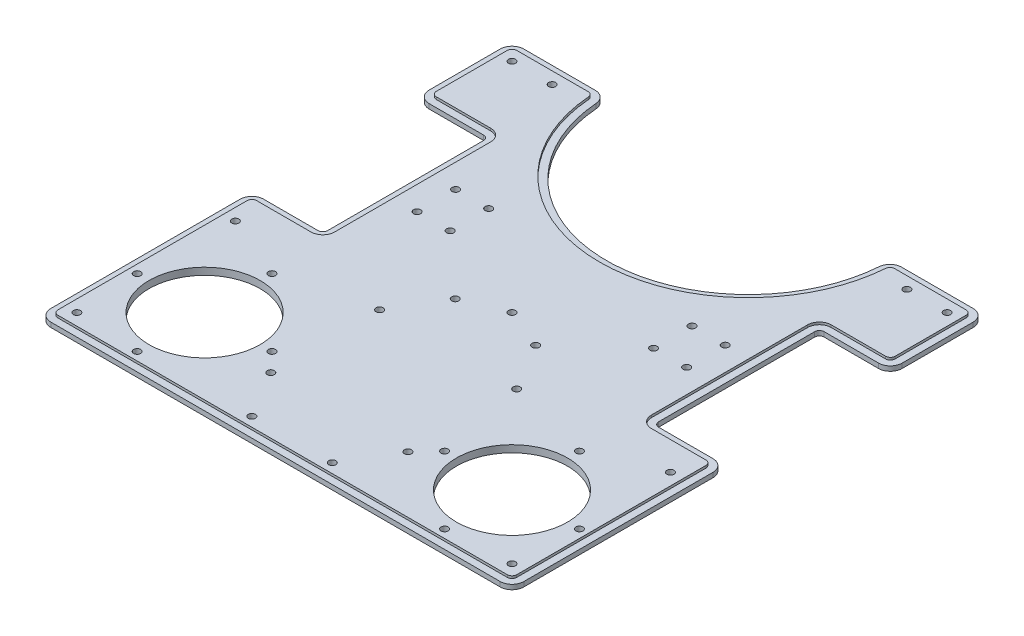
SolidWorks part; units mm, degrees
ref_plane "Front Plane" through (0, 0, 0) normal (0, 0, 1) x (1, 0, 0)
ref_plane "Top Plane" through (0, 0, 0) normal (0, 1, 0) x (1, 0, 0)
ref_plane "Right Plane" through (0, 0, 0) normal (1, 0, 0) x (0, 0, -1)
sketch "Sketch1" plane through (0, 0, 0) normal (0, 1, 0) x (1, 0, 0)
  line L0 (0, 100) -> (0, -100)
  line L1 (-100, -100) -> (100, -100)
  line L2 (-100, -100) -> (-100, 100)
  line L3 (-100, 100) -> (100, 100)
  line L4 (100, -100) -> (100, 100)
  line L5 (-100, -100) -> (100, 100) construction
  line L6 (-100, 100) -> (100, -100) construction
  line L7 (0, 0) -> (100, 0)
  line L8 (70, 25) -> (37.5, 25)
  line L9 (100, 60) -> (70, 60)
  line L10 (100, 60) -> (100, -10)
  line L11 (100, -10) -> (70, -10)
  line L12 (70, 60) -> (70, -10)
  line L13 (100, -65) -> (65, -65)
  line L14 (5, 11.85) -> (70, 11.85)
  line L15 (5, 11.85) -> (5, 38.15)
  line L16 (5, 38.15) -> (70, 38.15)
  line L17 (70, 11.85) -> (70, 38.15)
  line L18 (5, 11.85) -> (70, 38.15) construction
  line L19 (5, 38.15) -> (70, 11.85) construction
  line L20 (0, -50) -> (29, -50)
  line L21 (29, -93) -> (-29, -93)
  line L22 (29, -93) -> (29, -7)
  line L23 (29, -7) -> (-29, -7)
  line L24 (-29, -93) -> (-29, -7)
  line L25 (29, -93) -> (-29, -7) construction
  line L26 (29, -7) -> (-29, -93) construction
  line L27 (35, 38.15) -> (35, 11.85)
  line L28 (43, 38.15) -> (43, 11.85)
  line L29 (68, 11.85) -> (35, 11.85)
  line L30 (68, 11.85) -> (68, 38.15)
  line L31 (68, 38.15) -> (35, 38.15)
  line L32 (35, 11.85) -> (35, 38.15)
  line L33 (68, 11.85) -> (35, 38.15) construction
  line L34 (68, 38.15) -> (35, 11.85) construction
  line L35 (57, 38.15) -> (57, 11.85)
  line L36 (50, 38.15) -> (50, 11.85)
  line L37 (57, 38.15) -> (43, 38.15)
  line L38 (57, 38.15) -> (57, 11.85)
  line L39 (57, 11.85) -> (43, 11.85)
  line L40 (43, 38.15) -> (43, 11.85)
  circle A0 centre (0, 100) radius 60
  circle A1 centre (65, -65) radius 23.5
  circle A2 centre (65, -65) radius 28.5
  circle A3 centre (93.5, -65) radius 1.5
  circle A4 centre (17, -93) radius 1.5
  circle A5 centre (29, -73) radius 1.5
  circle A6 centre (57, 16.85) radius 1.5
  circle A7 centre (92, -92) radius 1.5
  circle A8 centre (92, -25) radius 1.5
  circle A9 centre (92, 92) radius 1.5
  circle A10 centre (75, 92) radius 1.5
  circle A11 centre (0, 0) radius 1.5
  point P0 (0, 0)
  point P27 (0, -50)
  point P40 (51.5, 25)
  dimension "D3" = 120
  dimension "D9" = 47
  dimension "D10" = 57
  dimension "D11" = 3
  dimension "D17" = 3
  dimension "D18" = 3
  dimension "D25" = 3
  dimension "D27" = 3
  dimension "D29" = 3
  dimension "D32" = 3
  dimension "D33" = 3
  dimension "D37" = 3
  dimension "D1" = 200
  dimension "D2" = 200
  dimension "D4" = 70
  dimension "D5" = 30
  dimension "D6" = 95
  dimension "D7" = 26.3
  dimension "D8" = 10
  dimension "D12" = 35
  dimension "D13" = 35
  dimension "D14" = 86
  dimension "D15" = 58
  dimension "D16" = 50
  dimension "D19" = 20
  dimension "D20" = 12
  dimension "D21" = 65
  dimension "D22" = 33
  dimension "D23" = 8
  dimension "D24" = 22
  dimension "D26" = 5
  dimension "D28" = 8
  dimension "D30" = 8
  dimension "D31" = 25
  dimension "D34" = 8
  dimension "D35" = 8
  dimension "D36" = 25
sketch "Sketch2" plane through (0, 0, 0) normal (0, 1, 0) x (1, 0, 0)
  line L0 (70, 25) -> (37.5, 25) construction
  line L1 (0, 0) -> (100, 0) construction
  line L2 (0, 100) -> (0, -100) construction
  line L3 (100, -65) -> (65, -65) construction
  line L4 (100, 60) -> (70, 60)
  line L5 (70, 60) -> (70, -10)
  line L6 (70, -10) -> (100, -10)
  line L7 (100, -10) -> (100, 60)
  line L8 (100, 60) -> (70, 60)
  line L9 (70, 60) -> (70, -10)
  line L10 (70, -10) -> (100, -10)
  line L11 (100, -10) -> (100, 60)
  line L12 (-100, -100) -> (100, -100)
  line L13 (100, -100) -> (100, 100)
  line L14 (100, 100) -> (-100, 100)
  line L15 (-100, 100) -> (-100, -100)
  line L16 (-100, -100) -> (100, -100)
  line L17 (100, -100) -> (100, 100)
  line L18 (100, 100) -> (60, 100)
  line L19 (-100, 100) -> (-100, -100)
  line L20 (-29, -93) -> (29, -93)
  line L21 (-29, -7) -> (-29, -93)
  line L22 (29, -7) -> (-29, -7)
  line L23 (29, -93) -> (29, -7)
  line L24 (-29, -93) -> (29, -93)
  line L25 (-29, -7) -> (-29, -93)
  line L26 (29, -7) -> (-29, -7)
  line L27 (29, -93) -> (29, -7)
  line L28 (5, 11.85) -> (70, 11.85)
  line L29 (70, 11.85) -> (70, 38.15)
  line L30 (70, 38.15) -> (5, 38.15)
  line L31 (5, 38.15) -> (5, 11.85)
  line L32 (5, 11.85) -> (70, 11.85)
  line L33 (70, 11.85) -> (70, 38.15)
  line L34 (70, 38.15) -> (5, 38.15)
  line L35 (5, 38.15) -> (5, 11.85)
  line L36 (57, 38.15) -> (57, 11.85) construction
  line L37 (57, 38.15) -> (57, 11.85) construction
  line L38 (57, 11.85) -> (43, 11.85) construction
  line L39 (57, 38.15) -> (43, 38.15) construction
  line L40 (43, 38.15) -> (43, 11.85) construction
  line L41 (43, 38.15) -> (43, 11.85) construction
  line L42 (35, 38.15) -> (35, 11.85) construction
  line L43 (68, 11.85) -> (35, 11.85) construction
  line L44 (68, 11.85) -> (68, 38.15) construction
  line L45 (68, 38.15) -> (35, 38.15) construction
  line L46 (35, 11.85) -> (35, 38.15) construction
  line L47 (0, -50) -> (29, -50) construction
  line L48 (50, 38.15) -> (50, 11.85) construction
  line L49 (70, 25) -> (37.5, 25)
  line L50 (0, 0) -> (100, 0)
  line L51 (0, 40) -> (0, -100)
  line L52 (100, -65) -> (65, -65)
  line L53 (57, 38.15) -> (57, 11.85)
  line L54 (57, 38.15) -> (57, 11.85)
  line L55 (57, 11.85) -> (43, 11.85)
  line L56 (57, 38.15) -> (43, 38.15)
  line L57 (43, 38.15) -> (43, 11.85)
  line L58 (43, 38.15) -> (43, 11.85)
  line L59 (35, 38.15) -> (35, 11.85)
  line L60 (68, 11.85) -> (35, 11.85)
  line L61 (68, 11.85) -> (68, 38.15)
  line L62 (68, 38.15) -> (35, 38.15)
  line L63 (35, 11.85) -> (35, 38.15)
  line L64 (0, -50) -> (29, -50)
  line L65 (50, 38.15) -> (50, 11.85)
  line L66 (-60, 100) -> (-100, 100)
  circle A1 centre (0, 100) radius 60
  arc A2 (-60, 100) -> (60, 100) centre (0, 100) ccw
  circle A3 centre (93.5, -65) radius 1.5
  circle A4 centre (93.5, -65) radius 1.5
  circle A5 centre (65, -65) radius 28.5
  circle A6 centre (65, -65) radius 28.5
  circle A7 centre (65, -65) radius 23.5
  circle A8 centre (65, -65) radius 23.5
  circle A9 centre (29, -73) radius 1.5
  circle A10 centre (29, -73) radius 1.5
  circle A11 centre (17, -93) radius 1.5
  circle A12 centre (17, -93) radius 1.5
  circle A13 centre (0, 0) radius 1.5
  circle A14 centre (0, 0) radius 1.5
  circle A15 centre (75, 92) radius 1.5
  circle A16 centre (75, 92) radius 1.5
  circle A17 centre (92, 92) radius 1.5
  circle A18 centre (92, 92) radius 1.5
  circle A19 centre (92, -25) radius 1.5
  circle A20 centre (92, -25) radius 1.5
  circle A21 centre (92, -92) radius 1.5
  circle A22 centre (92, -92) radius 1.5
  circle A23 centre (57, 16.85) radius 1.5
  circle A24 centre (57, 16.85) radius 1.5
  dimension "D1" = 0
  dimension "D2" = 0
  dimension "D3" = 0
  dimension "D4" = 0
  dimension "D5" = 0
  dimension "D6" = 0
  dimension "D7" = 0
  dimension "D8" = 0
  dimension "D9" = 0
  dimension "D10" = 0
  dimension "D11" = 0
  dimension "D12" = 0
  dimension "D13" = 0
  dimension "D14" = 0
  dimension "D15" = 0
  dimension "D16" = 0
sketch "Sketch3" plane through (0, 0, 0) normal (0, 1, 0) x (1, 0, 0)
  line L1 (-100, 100) -> (100, 100)
  line L2 (-100, 100) -> (-100, -100)
  line L3 (-100, -100) -> (100, -100)
  line L4 (100, 100) -> (100, -100)
extrude "Boss-Extrude1" add sketch "Sketch3" along normal blind 3
sketch "Sketch4" plane through (0, 3, 0) normal (0, 1, 0) x (1, 0, 0)
  line L0 (-100, -100) -> (100, 100) construction
  line L8 (-100, 100) -> (100, 100) construction
  line L9 (70, 60) -> (100, 60)
  line L10 (70, 60) -> (70, -10)
  line L11 (70, -10) -> (100, -10)
  line L12 (100, 60) -> (100, -10)
  circle A0 centre (92, 92) radius 1.5
  circle A1 centre (92, -92) radius 1.5
  circle A2 centre (-92, -92) radius 1.5
  circle A3 centre (-92, 92) radius 1.5
  circle A4 centre (92, -25) radius 1.5
  circle A5 centre (93.5, -65) radius 1.5
  circle A6 centre (17, -93) radius 1.5
  circle A7 centre (29, -73) radius 1.5
  circle A8 centre (75, 92) radius 1.5
  circle A9 centre (29, -27) radius 1.5
  circle A10 centre (17, -7) radius 1.5
  circle A11 centre (-92, -25) radius 1.5
  circle A12 centre (-17, -93) radius 1.5
  circle A13 centre (-29, -73) radius 1.5
  circle A14 centre (-29, -27) radius 1.5
  circle A15 centre (-17, -7) radius 1.5
  circle A16 centre (65, -65) radius 23.5
  circle A17 centre (65, -93.5) radius 1.5
  circle A18 centre (36.5, -65) radius 1.5
  circle A19 centre (65, -36.5) radius 1.5
  circle A20 centre (57, 16.85) radius 1.5
  circle A21 centre (57, 33.15) radius 1.5
  circle A22 centre (43, 16.85) radius 1.5
  circle A23 centre (43, 33.15) radius 1.5
  circle A24 centre (0, 100) radius 60
  circle A25 centre (-75, 92) radius 1.5
  circle A26 centre (0, 0) radius 1.5
  point P12 (0, 0)
  point P70 (65, -65)
  dimension "D1" = 4
  dimension "D2" = 4
extrude "Cut-Extrude1" cut sketch "Sketch4" against normal blind 5
ref_plane "Plane1" through (0, 0, 0) normal (-1, 0, 0) x (0, 0, 1)
mirror "Mirror1" about plane through (0, 0, 0) normal (-1, 0, 0) of "Cut-Extrude1"
fillet "Fillet1" radius 5 10 edges at (-100, 1.5, 100) (-100, 1.5, 10) (-100, 1.5, -60) (-100, 1.5, -100) (-60, 1.5, -100) (60, 1.5, -100) (100, 1.5, -60) (100, 1.5, -100) (100, 1.5, 100) (100, 1.5, 10)
fillet "Fillet2" radius 2 4 edges at (-70, 1.5, 10) (-70, 1.5, -60) (70, 1.5, -60) (70, 1.5, 10)
sketch "Sketch5" plane through (0, 3, 0) normal (0, 1, 0) x (1, 0, 0)
  line L0 (-97, 95) -> (-97, 65)
  line L1 (-95, 63) -> (-72, 63)
  line L2 (-67, 58) -> (-67, -8)
  line L3 (-72, -13) -> (-95, -13)
  line L4 (-97, -15) -> (-97, -95)
  line L5 (-95, -97) -> (95, -97)
  line L6 (97, -95) -> (97, -15)
  line L7 (95, -13) -> (72, -13)
  line L8 (67, -8) -> (67, 58)
  line L9 (72, 63) -> (95, 63)
  line L10 (97, 65) -> (97, 95)
  line L11 (95, 97) -> (64.8074, 97)
  line L12 (-64.8074, 97) -> (-95, 97)
  line L13 (-95, -100) -> (95, -100)
  line L14 (100, -95) -> (100, -15)
  line L15 (95, -10) -> (72, -10)
  line L16 (70, -8) -> (70, 58)
  line L17 (72, 60) -> (95, 60)
  line L18 (100, 65) -> (100, 95)
  line L19 (95, 100) -> (64.8074, 100)
  line L20 (-64.8074, 100) -> (-95, 100)
  line L21 (-100, 95) -> (-100, 65)
  line L22 (-95, 60) -> (-72, 60)
  line L23 (-70, 58) -> (-70, -8)
  line L24 (-72, -10) -> (-95, -10)
  line L25 (-100, -15) -> (-100, -95)
  line L26 (-95, -100) -> (95, -100)
  line L27 (100, -95) -> (100, -15)
  line L28 (95, -10) -> (72, -10)
  line L29 (70, -8) -> (70, 58)
  line L30 (72, 60) -> (95, 60)
  line L31 (100, 65) -> (100, 95)
  line L32 (95, 100) -> (64.8074, 100)
  line L33 (-64.8074, 100) -> (-95, 100)
  line L34 (-100, 95) -> (-100, 65)
  line L35 (-95, 60) -> (-72, 60)
  line L36 (-70, 58) -> (-70, -8)
  line L37 (-72, -10) -> (-95, -10)
  line L38 (-100, -15) -> (-100, -95)
  arc A0 (-97, 65) -> (-95, 63) centre (-95, 65) ccw
  arc A1 (-67, 58) -> (-72, 63) centre (-72, 58) ccw
  arc A2 (-72, -13) -> (-67, -8) centre (-72, -8) ccw
  arc A3 (-95, -13) -> (-97, -15) centre (-95, -15) ccw
  arc A4 (-97, -95) -> (-95, -97) centre (-95, -95) ccw
  arc A5 (95, -97) -> (97, -95) centre (95, -95) ccw
  arc A6 (97, -15) -> (95, -13) centre (95, -15) ccw
  arc A7 (67, -8) -> (72, -13) centre (72, -8) ccw
  arc A8 (72, 63) -> (67, 58) centre (72, 58) ccw
  arc A9 (95, 63) -> (97, 65) centre (95, 65) ccw
  arc A10 (97, 95) -> (95, 97) centre (95, 95) ccw
  arc A11 (64.8074, 97) -> (62.8133, 95.1538) centre (64.8074, 95) ccw
  arc A12 (-62.8133, 95.1538) -> (62.8133, 95.1538) centre (0, 100) ccw
  arc A13 (-62.8133, 95.1538) -> (-64.8074, 97) centre (-64.8074, 95) ccw
  arc A14 (-95, 97) -> (-97, 95) centre (-95, 95) ccw
  arc A15 (95, -100) -> (100, -95) centre (95, -95) ccw
  arc A16 (100, -15) -> (95, -10) centre (95, -15) ccw
  arc A17 (70, -8) -> (72, -10) centre (72, -8) ccw
  arc A18 (72, 60) -> (70, 58) centre (72, 58) ccw
  arc A19 (95, 60) -> (100, 65) centre (95, 65) ccw
  arc A20 (100, 95) -> (95, 100) centre (95, 95) ccw
  arc A21 (64.8074, 100) -> (59.8222, 95.3846) centre (64.8074, 95) ccw
  arc A22 (-59.8222, 95.3846) -> (59.8222, 95.3846) centre (0, 100) ccw
  arc A23 (-59.8222, 95.3846) -> (-64.8074, 100) centre (-64.8074, 95) ccw
  arc A24 (-95, 100) -> (-100, 95) centre (-95, 95) ccw
  arc A25 (-100, 65) -> (-95, 60) centre (-95, 65) ccw
  arc A26 (-70, 58) -> (-72, 60) centre (-72, 58) ccw
  arc A27 (-72, -10) -> (-70, -8) centre (-72, -8) ccw
  arc A28 (-95, -10) -> (-100, -15) centre (-95, -15) ccw
  arc A29 (-100, -95) -> (-95, -100) centre (-95, -95) ccw
  arc A30 (95, -100) -> (100, -95) centre (95, -95) ccw
  arc A31 (100, -15) -> (95, -10) centre (95, -15) ccw
  arc A32 (70, -8) -> (72, -10) centre (72, -8) ccw
  arc A33 (72, 60) -> (70, 58) centre (72, 58) ccw
  arc A34 (95, 60) -> (100, 65) centre (95, 65) ccw
  arc A35 (100, 95) -> (95, 100) centre (95, 95) ccw
  arc A36 (64.8074, 100) -> (59.8222, 95.3846) centre (64.8074, 95) ccw
  arc A37 (-59.8222, 95.3846) -> (59.8222, 95.3846) centre (0, 100) ccw
  arc A38 (-59.8222, 95.3846) -> (-64.8074, 100) centre (-64.8074, 95) ccw
  arc A39 (-95, 100) -> (-100, 95) centre (-95, 95) ccw
  arc A40 (-100, 65) -> (-95, 60) centre (-95, 65) ccw
  arc A41 (-70, 58) -> (-72, 60) centre (-72, 58) ccw
  arc A42 (-72, -10) -> (-70, -8) centre (-72, -8) ccw
  arc A43 (-95, -10) -> (-100, -15) centre (-95, -15) ccw
  arc A44 (-100, -95) -> (-95, -100) centre (-95, -95) ccw
  dimension "D1" = 0
  dimension "D2" = 3
extrude "Cut-Extrude2" cut sketch "Sketch5" against normal blind 1
sketch "Sketch6" plane through (0, 3, 0) normal (0, 1, 0) x (1, 0, 0)
  text T0 "<b>PAO</b>" font "Century Gothic" height 15
extrude "Cut-Extrude3" [suppressed] cut sketch "Sketch6" against normal blind 1
